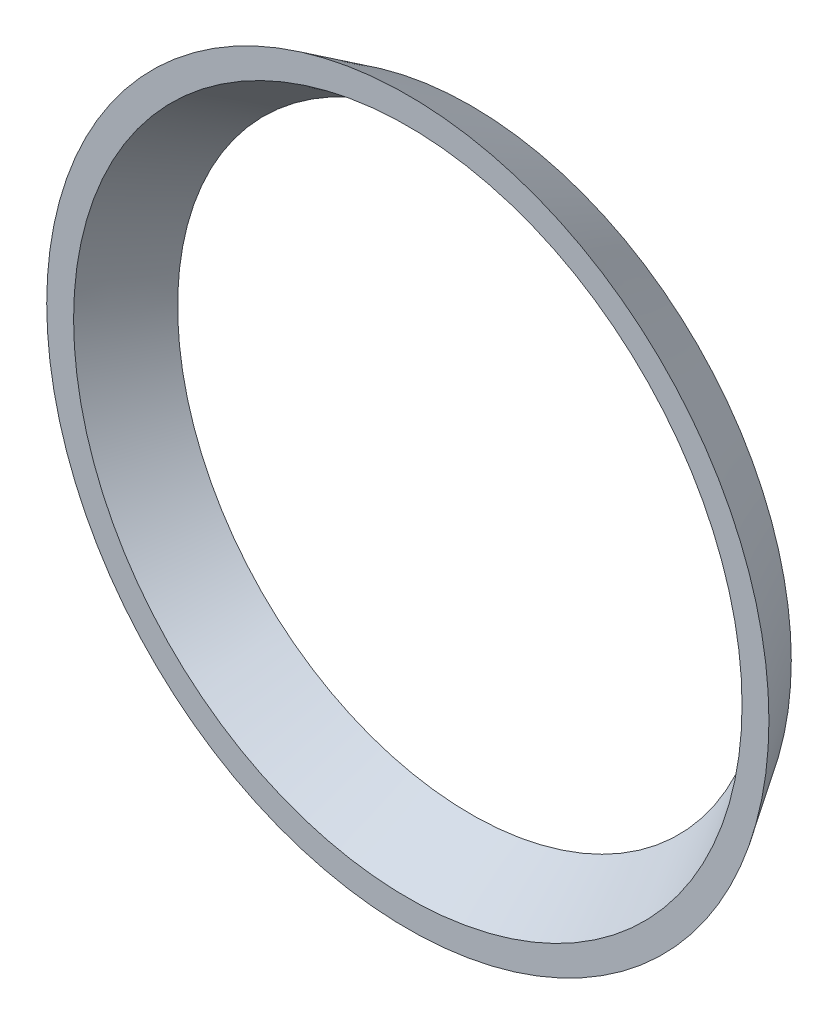
SolidWorks part; units mm, degrees
material "Polyurethane"
ref_plane "Front Plane" through (0, 0, 0) normal (0, 0, 1) x (1, 0, 0)
ref_plane "Top Plane" through (0, 0, 0) normal (0, 1, 0) x (1, 0, 0)
ref_plane "Right Plane" through (0, 0, 0) normal (1, 0, 0) x (0, 0, -1)
sketch "Sketch1" plane through (0, 0, 0) normal (1, 0, 0) x (0, 0, -1)
  line L0 (0, 0) -> (6.792, 0) construction
  line L1 (0, 18.5117) -> (3.5, 16.25)
  line L2 (0, 18.5117) -> (0, 20)
  line L3 (0, 20) -> (3.5, 17.7383)
  line L4 (3.5, 16.25) -> (3.5, 17.7383)
  dimension "D1" = 32.5
  dimension "D2" = 40
  dimension "D3" = 3.5
  dimension "D4" = 1.25
revolve "Revolve1" add sketch "Sketch1" angle 360 about L0
